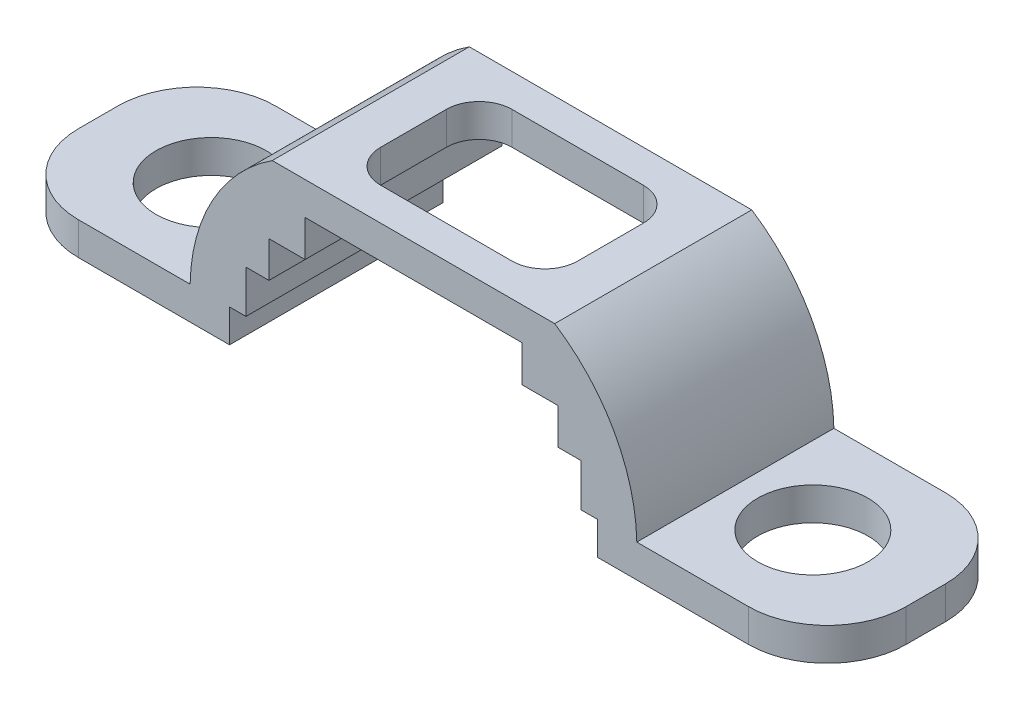
SolidWorks part; units mm, degrees
material "PLA"
ref_plane "Front Plane" through (0, 0, 0) normal (0, 0, 1) x (1, 0, 0)
ref_plane "Top Plane" through (0, 0, 0) normal (0, 1, 0) x (1, 0, 0)
ref_plane "Right Plane" through (0, 0, 0) normal (1, 0, 0) x (0, 0, -1)
sketch "Sketch1" plane through (0, 0, 0) normal (0, 0, 1) x (1, 0, 0)
  line L0 (-63, 4.5) -> (-28, 4.5)
  line L1 (-28, 4.5) -> (-28, 9.5)
  line L2 (-28, 9.5) -> (-25.5, 9.5)
  line L3 (-25.5, 9.5) -> (-25.5, 16)
  line L4 (-25.5, 16) -> (-22, 16)
  line L5 (-22, 16) -> (-22, 21.5)
  line L6 (-22, 21.5) -> (-16.5, 21.5)
  line L7 (-16.5, 21.5) -> (-16.5, 27.05)
  line L8 (-16.5, 27.05) -> (0, 27.05)
  circle A0 centre (0, 0) radius 27.05
  dimension "D1" = 54.1
  dimension "D2" = 35
  dimension "D3" = 4.5
  dimension "D4" = 28
  dimension "D5" = 5
  dimension "D6" = 2.5
  dimension "D7" = 6.5
  dimension "D8" = 3.5
  dimension "D9" = 5.5
  dimension "D10" = 5.5
  dimension "D11" = 16.5
  dimension "D12" = 5.55
extrude "Extrude-Thin1" add sketch "Sketch1" along normal mid plane 30 thin contours L0 L1 L2 L3 L4 L5 L6 L7 L8
sketch "Sketch2" plane through (0, 9.5, 0) normal (0, 1, 0) x (1, 0, 0)
  line L0 (0, -15) -> (0, 15) construction
  circle A0 centre (-45.8, 0) radius 8.4
  dimension "D1" = 16.8
  dimension "D2" = 45.8
extrude "Cut-Extrude1" cut sketch "Sketch2" against normal through all
fillet "Fillet1" radius 12 2 edges at (-63, 7, -15) (-63, 7, 15)
mirror "Mirror1" about plane through (0, 32.05, 15) normal (1, 0, 0) of "Fillet1", "Cut-Extrude1", "Extrude-Thin1"
sketch "Sketch3" plane through (0, 32.05, 0) normal (0, 1, 0) x (1, 0, 0)
  line L1 (15, -10) -> (-15, -10)
  line L2 (15, -10) -> (15, 10)
  line L3 (15, 10) -> (-15, 10)
  line L4 (-15, -10) -> (-15, 10)
  line L5 (15, -10) -> (-15, 10) construction
  line L6 (15, 10) -> (-15, -10) construction
  point P0 (0, 0)
  dimension "D1" = 30
  dimension "D2" = 20
extrude "Cut-Extrude2" cut sketch "Sketch3" against normal through all
sketch "Sketch4" plane through (0, 0, 15) normal (0, 0, 1) x (1, 0, 0)
  line L0 (-51, 9.5) -> (-33, 9.5) construction
  line L1 (-51, 9.5) -> (-51, 4.5) construction
  line L2 (-21.5, 26.5) -> (-21.5, 32.05) construction
  line L3 (-27, 26.5) -> (-21.5, 26.5) construction
  line L4 (-27, 21) -> (-27, 26.5) construction
  line L5 (-30.5, 21) -> (-27, 21) construction
  line L6 (-30.5, 14.5) -> (-30.5, 21) construction
  line L7 (-33, 14.5) -> (-30.5, 14.5) construction
  line L8 (-33, 9.5) -> (-33, 14.5) construction
  line L9 (-21.5, 26.5) -> (-21.5, 32.05)
  line L10 (-27, 26.5) -> (-21.5, 26.5)
  line L11 (-27, 21) -> (-27, 26.5)
  line L12 (-30.5, 21) -> (-27, 21)
  line L13 (-30.5, 14.5) -> (-30.5, 21)
  line L14 (-33, 14.5) -> (-30.5, 14.5)
  line L15 (-33, 9.5) -> (-33, 14.5)
  line L16 (-34, 9.5) -> (-33, 9.5)
  arc A0 (-34, 9.5) -> (-21.5, 32.05) centre (-6.5046, 8.9982) cw
  dimension "D1" = 27.5
  dimension "D2" = 17
extrude "Boss-Extrude1" add sketch "Sketch4" against normal up to surface (30 mm away) up to face at (0, 16.95, -15)
mirror "Mirror2" about plane through (0, 0, 0) normal (1, 0, 0) of "Boss-Extrude1"
fillet "Fillet2" radius 5 4 edges at (-15, 29.55, 10) (15, 29.55, 10) (15, 29.55, -10) (-15, 29.55, -10)
